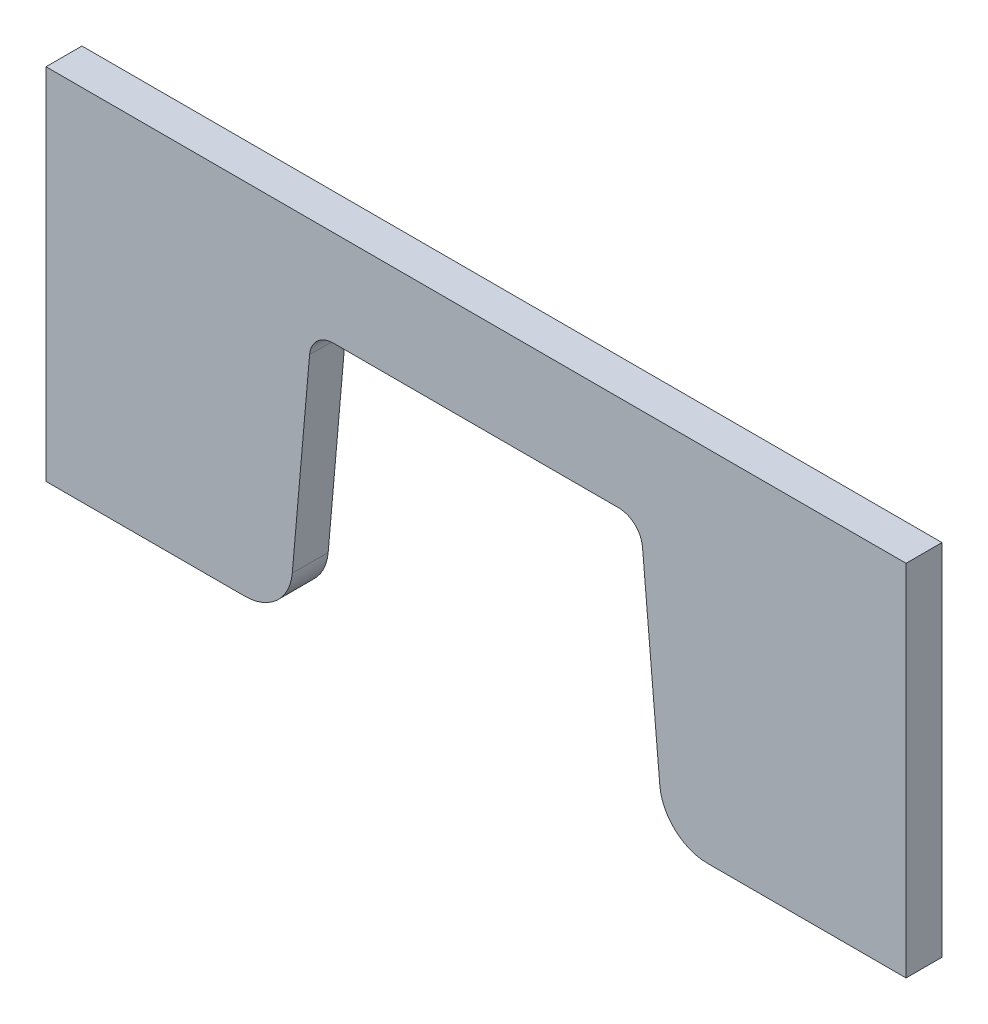
SolidWorks part; units mm, degrees
material "MDF"
ref_plane "Front Plane" through (0, 0, 0) normal (0, 0, 1) x (1, 0, 0)
ref_plane "Top Plane" through (0, 0, 0) normal (0, 1, 0) x (1, 0, 0)
ref_plane "Right Plane" through (0, 0, 0) normal (1, 0, 0) x (0, 0, -1)
sketch "Sketch1" plane through (0, 0, 0) normal (0, 0, 1) x (1, 0, 0)
  line L0 (-228.0888, -463.55) -> (-126.4888, -463.55) construction
  line L1 (-126.4888, -463.55) -> (-122.7761, -463.55) construction
  line L2 (-97.4727, -440.3638) -> (-88.2891, -335.3948) construction
  line L3 (-61.8749, -323.8017) -> (-75.6375, -323.8017) construction
  line L4 (61.8749, -323.8017) -> (-61.8749, -323.8017) construction
  line L5 (61.8749, -323.8017) -> (75.6375, -323.8017) construction
  line L6 (97.4727, -440.3638) -> (88.2891, -335.3948) construction
  line L7 (126.4888, -463.55) -> (122.7761, -463.55) construction
  line L8 (228.0888, -463.55) -> (126.4888, -463.55) construction
  line L9 (-228.0888, -463.55) -> (-126.4888, -463.55)
  line L10 (-126.4888, -463.55) -> (-122.7761, -463.55)
  line L11 (-97.4727, -440.3638) -> (-88.2891, -335.3948)
  line L12 (-61.8749, -323.8017) -> (-75.6375, -323.8017)
  line L13 (61.8749, -323.8017) -> (-61.8749, -323.8017)
  line L14 (61.8749, -323.8017) -> (75.6375, -323.8017)
  line L15 (97.4727, -440.3638) -> (88.2891, -335.3948)
  line L16 (126.4888, -463.55) -> (122.7761, -463.55)
  line L17 (228.0888, -463.55) -> (126.4888, -463.55)
  line L18 (228.0888, -463.55) -> (228.0888, -273.05)
  line L19 (228.0888, 0) -> (228.0888, -437.7788) construction
  line L20 (228.0888, -273.05) -> (-228.0888, -273.05)
  line L21 (-228.0888, 0) -> (-228.0888, -437.7788) construction
  line L22 (-228.0888, -273.05) -> (-228.0888, -463.55)
  arc A0 (-122.7761, -463.55) -> (-113.7888, -461.9069) centre (-122.7761, -438.15) ccw construction
  arc A1 (-113.7888, -461.9069) -> (-97.4727, -440.3638) centre (-122.7761, -438.15) ccw construction
  arc A2 (-75.6375, -323.8017) -> (-88.2891, -335.3948) centre (-75.6375, -336.5017) ccw construction
  arc A3 (88.2891, -335.3948) -> (75.6375, -323.8017) centre (75.6375, -336.5017) ccw construction
  arc A6 (-122.7761, -463.55) -> (-113.7888, -461.9069) centre (-122.7761, -438.15) ccw
  arc A7 (-113.7888, -461.9069) -> (-97.4727, -440.3638) centre (-122.7761, -438.15) ccw
  arc A8 (-75.6375, -323.8017) -> (-88.2891, -335.3948) centre (-75.6375, -336.5017) ccw
  arc A9 (88.2891, -335.3948) -> (75.6375, -323.8017) centre (75.6375, -336.5017) ccw
  arc A10 (97.4727, -440.3638) -> (113.7888, -461.9069) centre (122.7761, -438.15) ccw
  arc A11 (113.7888, -461.9069) -> (122.7761, -463.55) centre (122.7761, -438.15) ccw
  dimension "D1" = 190.5
extrude "Boss-Extrude1" add sketch "Sketch1" along normal blind 19.05
